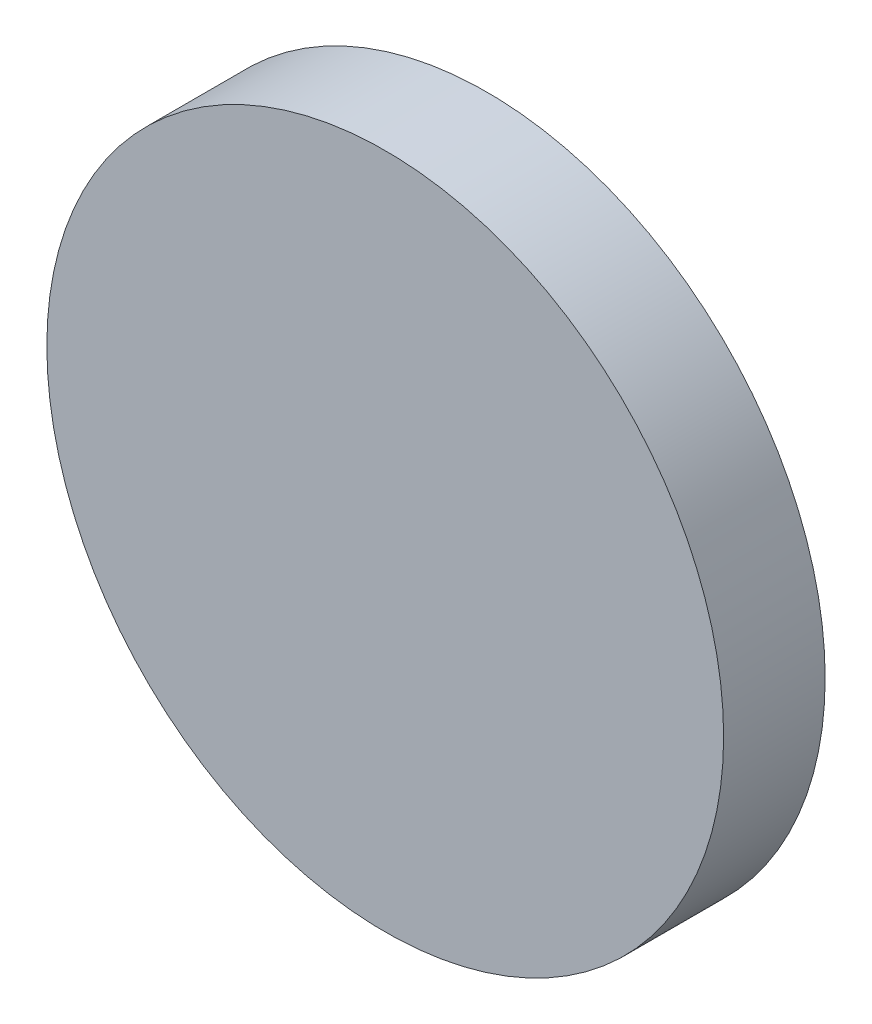
SolidWorks part; units mm, degrees
ref_plane "前基準面" through (0, 0, 0) normal (0, 0, 1) x (1, 0, 0)
ref_plane "上基準面" through (0, 0, 0) normal (0, 1, 0) x (1, 0, 0)
ref_plane "右基準面" through (0, 0, 0) normal (1, 0, 0) x (0, 0, -1)
sketch "草圖1" plane through (0, 0, 0) normal (0, 0, 1) x (1, 0, 0)
  circle A2 centre (0, 0) radius 100
extrude "填料-伸長2" add sketch "草圖1" along normal mid plane 30 contours A2
